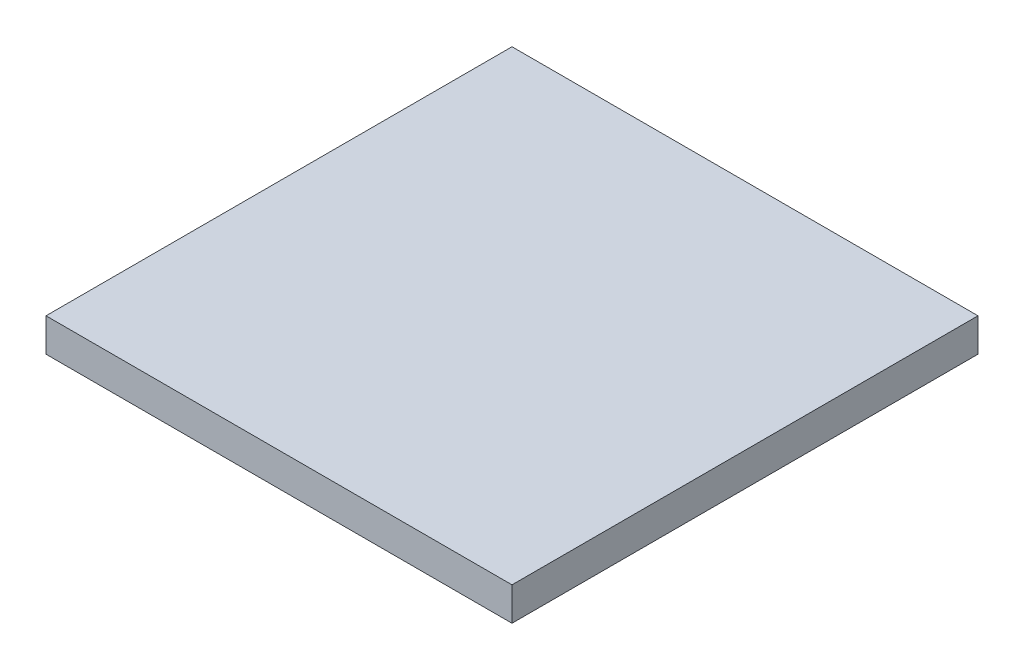
SolidWorks part; units mm, degrees
ref_plane "Front Plane" through (0, 0, 0) normal (0, 0, 1) x (1, 0, 0)
ref_plane "Top Plane" through (0, 0, 0) normal (0, 1, 0) x (1, 0, 0)
ref_plane "Right Plane" through (0, 0, 0) normal (1, 0, 0) x (0, 0, -1)
sketch "Sketch1" plane through (0, 0, 0) normal (0, 1, 0) x (1, 0, 0)
  line L1 (0, 0) -> (14, 0)
  line L2 (0, 0) -> (0, -14)
  line L3 (0, -14) -> (14, -14)
  line L4 (14, 0) -> (14, -14)
  dimension "D1" = 14
  dimension "D2" = 14
extrude "Boss-Extrude1" add sketch "Sketch1" along normal blind 1
